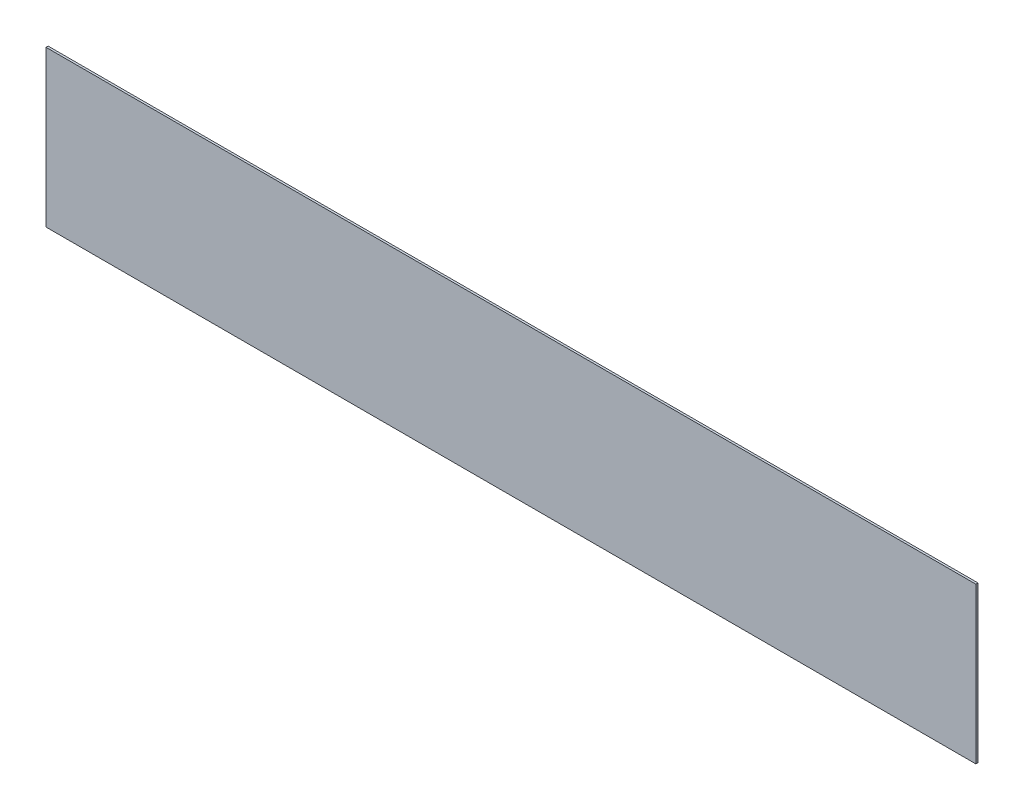
SolidWorks part; units mm, degrees
ref_plane "Front Plane" through (0, 0, 0) normal (0, 0, 1) x (1, 0, 0)
ref_plane "Top Plane" through (0, 0, 0) normal (0, 1, 0) x (1, 0, 0)
ref_plane "Right Plane" through (0, 0, 0) normal (1, 0, 0) x (0, 0, -1)
other "Configuration Table"
sketch "Sketch1" plane through (0, 0, 0) normal (0, 0, 1) x (1, 0, 0)
  line L1 (21.5, 10) -> (678.5, 10)
  line L2 (21.5, 10) -> (21.5, 120)
  line L3 (21.5, 120) -> (678.5, 120)
  line L4 (678.5, 10) -> (678.5, 120)
extrude "PACK_plint_arka_1" add sketch "Sketch1" against normal blind 1.5 from offset 798.5 separate body
